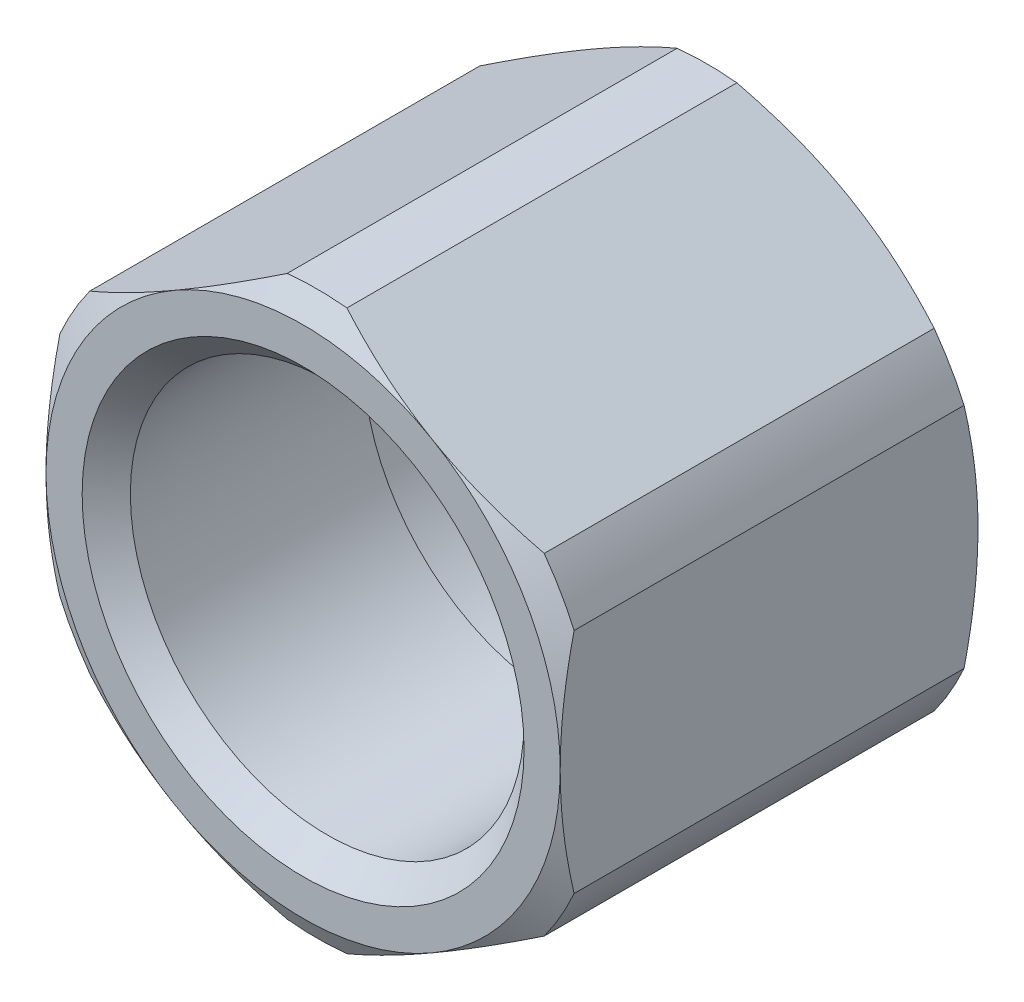
SolidWorks part; units mm, degrees
material "2024 Сплав"
ref_plane "Спереди" through (0, 0, 0) normal (0, 0, 1) x (1, 0, 0)
ref_plane "Сверху" through (0, 0, 0) normal (0, 1, 0) x (1, 0, 0)
ref_plane "Справа" through (0, 0, 0) normal (1, 0, 0) x (0, 0, -1)
sketch "Эскиз1" plane through (0, 0, 0) normal (0, 0, 1) x (1, 0, 0)
  line L7 (0, 18.4752) -> (-16, 9.2376)
  line L8 (-16, 9.2376) -> (-16, -9.2376)
  line L9 (-16, -9.2376) -> (0, -18.4752)
  line L10 (0, -18.4752) -> (16, -9.2376)
  line L11 (16, -9.2376) -> (16, 9.2376)
  line L12 (16, 9.2376) -> (0, 18.4752)
  circle A0 centre (0, 0) radius 12.25
  circle A1 centre (0, 0) radius 16 construction
  circle A2 centre (0, 0) radius 17.5 construction
  dimension "D1" = 32
  dimension "D2" = 24.5
  dimension "D3" = 35
extrude "Бобышка-Вытянуть1" add sketch "Эскиз1" along normal blind 26
sketch "Эскиз2" plane through (0, 0, 0) normal (1, 0, 0) x (0, 0, -1)
  line L0 (0, 19.828) -> (-2.2101, 19.828)
  line L1 (0, 16) -> (0, 19.828)
  line L2 (-2.2101, 19.828) -> (0, 16)
  line L3 (0, 0) -> (-26, 0) construction
  line L4 (-13, 0) -> (-13, 18) construction
  line L6 (-23.7899, 19.828) -> (-26, 16)
  line L7 (-26, 16) -> (-26, 19.828)
  line L8 (-26, 19.828) -> (-23.7899, 19.828)
  dimension "D1" = 16
  dimension "D2" = 30
revolve "Вырез-Повернуть1" cut sketch "Эскиз2" angle 360 about L3
sketch "Эскиз7" plane through (0, 0, 26) normal (0, 0, 1) x (1, 0, 0)
  circle A0 centre (0, 0) radius 17.5
  dimension "D1" = 35
extrude "Вырез-Вытянуть2" cut sketch "Эскиз7" against normal through all flip side to cut
sketch "Эскиз3" plane through (0, 0, 0) normal (1, 0, 0) x (0, 0, -1)
  line L2 (-9.5, 13.1) -> (-11.1454, 10.25)
  line L3 (-11.1454, 10.25) -> (0.7588, 10.25)
  line L4 (-6.5, 13.1) -> (-9.5, 13.1)
  line L5 (0, 0) -> (-26, 0) construction
  line L6 (-26, 12.25) -> (-26, -12.25) construction
  line L7 (-6.5, 12.1) -> (-6.5, 0) construction
  line L12 (-4.1113, 12.25) -> (0.7588, 13.8324)
  line L15 (0.7588, 10.25) -> (0.7588, 13.8324)
  line L17 (-5.5113, 12.25) -> (-4.1113, 12.25)
  arc A0 (-5.5113, 12.25) -> (-6.5, 13.1) centre (-6.5, 12.1) ccw
  dimension "D7" = 2
  dimension "D1" = 3
  dimension "D2" = 10.25
  dimension "D3" = 24.5
  dimension "D4" = 13.1
  dimension "D5" = 60
  dimension "D6" = 18
  dimension "D8" = 1.4
  dimension "D9" = 16.5
revolve "Вырез-Повернуть2" cut sketch "Эскиз3" angle 360 about L5
chamfer "Фаска1" distance 1.5 angle 45 1 edges at (12.25, 0, 26)
